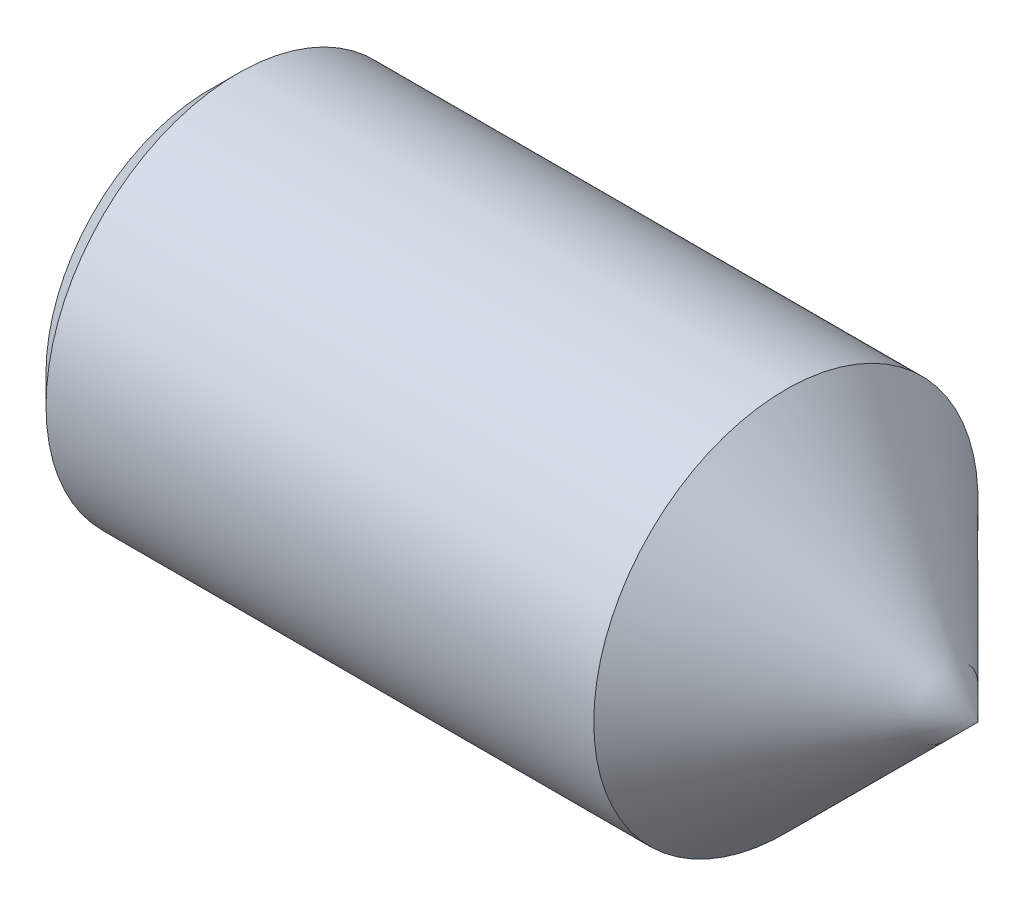
SolidWorks part; units mm, degrees
revolve "BaseBody" add sketch "BodySke" angle 360 about L5
sketch "BodySke" plane through (0, 0, 0) normal (0, 0, 1) x (1, 0, 0)
  line L0 (0, 0) -> (0, 10.8102)
  line L1 (0, 10.8102) -> (1.8898, 12.7)
  line L2 (1.8898, 12.7) -> (38.1, 12.7)
  line L3 (38.1, 12.7) -> (50.8, 0)
  line L4 (50.8, 0) -> (0, 0)
  line L5 (-12.7, 0) -> (88.9, 0) construction
  line L6 (38.1, -12.7) -> (50.8, 0) construction
  line L7 (1.0541, 15.875) -> (1.0541, -3.175) construction
  line L8 (0, -10.8102) -> (1.8898, -12.7) construction
  dimension "Cone_ang" = 90
  dimension "Length" = 50.8
  dimension "Diameter" = 25.4
  dimension "Drive_ch_ang" = 45
  dimension "Minor_dia" = 21.6205
  dimension "Advance" = 2.1082
cosmetic thread "ThreadCosmetic" [suppressed] parameters "Thread_minor"=21.6205
ref_plane "Plane1" through (0, 0, 0) normal (0, 0, 1) x (1, 0, 0)
ref_plane "Plane2" through (0, 0, 0) normal (0, 1, 0) x (1, 0, 0)
ref_plane "Plane3" through (0, 0, 0) normal (1, 0, 0) x (0, 0, -1)
sketch "Sketch2" plane through (0, 0, 0) normal (-1, 0, 0) x (0, 0, 1)
  line L0 (4.1208, 7.1374) -> (-4.1208, 7.1374)
  line L1 (-4.1208, 7.1374) -> (-8.2416, 0)
  line L2 (4.1208, 7.1374) -> (8.2416, 0)
  line L3 (4.1208, -7.1374) -> (8.2416, 0)
  line L4 (4.1208, -7.1374) -> (-4.1208, -7.1374)
  line L5 (-4.1208, -7.1374) -> (-8.2416, 0)
  dimension "Hex_size" = 14.2748
  dimension "D2" = 7.1374
  dimension "D3" = 7.1374
extrude "Hex" cut sketch "Sketch2" against normal blind 14.2748
sketch "Sketch4" plane through (0, 4.7709, -0.5249) normal (-1, 0, 0) x (0, 0, 1)
  line L0 (0.5249, -4.7709) -> (10.6976, -4.7709)
  line L1 (0.5249, -4.7709) -> (6.6732, -1.2211) construction
  line L2 (0.5249, -4.7709) -> (5.6112, 4.0389)
  line L3 (8.9666, -2.6687) -> (10.2861, -1.9069)
  line L4 (6.5663, 1.4888) -> (7.8858, 2.2506)
  arc A0 (8.9666, -2.6687) -> (6.5663, 1.4888) centre (0.5249, -4.7709) ccw
  arc A1 (10.6976, -4.7709) -> (10.2861, -1.9069) centre (0.5249, -4.7709) ccw
  arc A2 (5.6112, 4.0389) -> (7.8858, 2.2506) centre (0.5249, -4.7709) cw
  circle A3 centre (0.5249, -4.7709) radius 8.6995 construction
  circle A4 centre (0.5249, -4.7709) radius 10.1727 construction
  dimension "Spline_n_dim" = 17.399
  dimension "Spline_m_dim" = 20.3454
  dimension "D1" = 30
  dimension "Spline_a_dim" = 60
  dimension "Spline_p_dim" = 4.8006
  dimension "D3" = 2.4003
extrude "Spline" [suppressed] cut sketch "Sketch4" against normal blind 12.7
pattern_circular "CirPattern1" [suppressed] count 6 every 60 about axis through (-12.7, 0, 0) along (1, 0, 0)
sketch "ThdSchSke" plane through (0, 0, 0) normal (0, 0, 1) x (1, 0, 0)
  line L0 (1.8898, -10.8102) -> (0.5665, -12.7)
  line L1 (1.8898, -10.8102) -> (3.213, -12.7)
  line L2 (3.213, -12.7) -> (3.213, -15.875)
  line L3 (-3.175, 0) -> (5.1513, 0) construction
  line L4 (1.8898, 12.7) -> (1.8898, -12.7) construction
  line L5 (3.213, -15.875) -> (0.5665, -15.875)
  line L6 (0.5665, -15.875) -> (0.5665, -12.7)
  dimension "Thread_minor" = 21.6205
  dimension "Diameter" = 25.4
revolve "ThreadSchematic" [suppressed] cut sketch "ThdSchSke" angle 360 about L3
pattern_linear "ThdSchPat" [suppressed]
equation "\"D2@Sketch2\" = \"Hex_size@Sketch2\" / 2"
equation "\"D3@Sketch2\" = \"Hex_size@Sketch2\" / 2"
equation "\"Thread_minor@ThreadCosmetic\" = \"Minor_dia@BodySke\""
equation "\"D1@Sketch4\" = \"Spline_a_dim@Sketch4\" / 2"
equation "\"D3@Sketch4\" = \"Spline_p_dim@Sketch4\" / 2"
equation "\"D2@CirPattern1\" = \"Spline_a_dim@Sketch4\""
equation "\"Num_teeth@CirPattern1\" = 360 / \"D2@CirPattern1\""
equation "\"Thread_minor@ThdSchSke\" = \"Thread_minor@ThreadCosmetic\""
equation "\"Diameter@ThdSchSke\" = \"Diameter@BodySke\""
equation "\"Overcut@ThdSchSke\" = \"Diameter@BodySke\" * 1.25"
equation "\"Num_threads@ThdSchPat\" = int( (\"Length@BodySke\" - ( ( ( \"Diameter@BodySke\" - \"Minor_dia@BodySke\" ) * 0.5 ) / tan( \"Drive_ch_ang@BodySke\" * 0.017453292 ) ) - ( ( \"Diameter@BodySke\" * 0.5 ) / tan( \"Cone_ang@BodySke\" * 0.008726646 ) ) ) / \"Advance@BodySke\" + 0.999 )  + 1"
equation "\"Advance@ThdSchPat\" = (\"Length@BodySke\" - ( ( ( \"Diameter@BodySke\" - \"Minor_dia@BodySke\" ) * 0.5 ) / tan( \"Drive_ch_ang@BodySke\" * 0.017453292 ) ) - ( ( \"Diameter@BodySke\" * 0.5 ) / tan( \"Cone_ang@BodySke\" * 0.008726646 ) ) ) /  (\"Num_threads@ThdSchPat\" - 1) 'relax it"
equation "' \"Num_threads@ThdSchPat\" = \"Num_threads@ThdSchPat\" - sgn( \"Num_threads@ThdSchPat\" - 1) '---chamfered tips only---"
